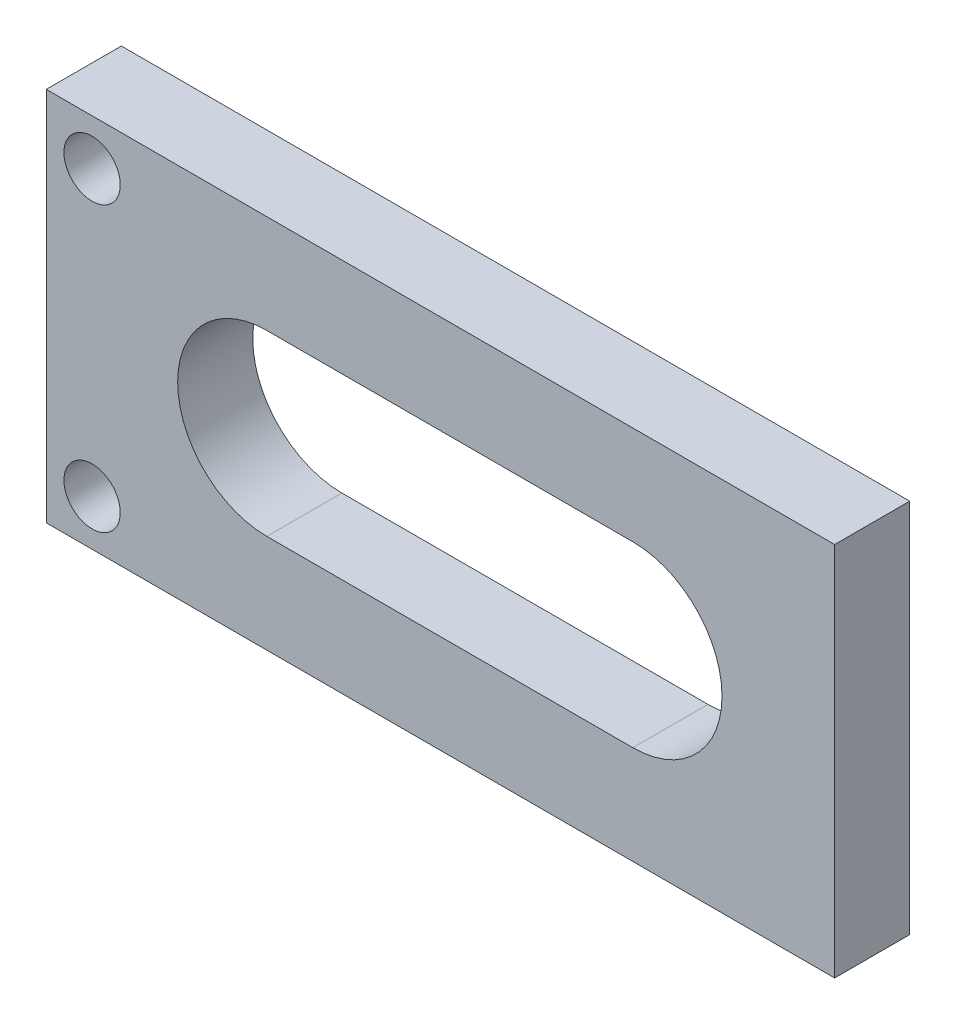
SolidWorks part; units mm, degrees
ref_plane "Front Plane" through (0, 0, 0) normal (0, 0, 1) x (1, 0, 0)
ref_plane "Top Plane" through (0, 0, 0) normal (0, 1, 0) x (1, 0, 0)
ref_plane "Right Plane" through (0, 0, 0) normal (1, 0, 0) x (0, 0, -1)
sketch "Sketch1" plane through (0, 0, 0) normal (0, 0, 1) x (1, 0, 0)
  line L0 (-9.25, 0) -> (10.25, 0) construction
  line L1 (-21, 10) -> (21, 10)
  line L2 (-21, 10) -> (-21, -10)
  line L3 (-21, -10) -> (21, -10)
  line L4 (21, 10) -> (21, -10)
  line L5 (-21, 10) -> (21, -10) construction
  line L6 (-21, -10) -> (21, 10) construction
  line L7 (-9.25, 4.75) -> (10.25, 4.75)
  line L8 (-9.25, -4.75) -> (10.25, -4.75)
  line L9 (55, 0) -> (-55, 0) construction
  arc A2 (-9.25, 4.75) -> (-9.25, -4.75) centre (-9.25, 0) ccw
  arc A3 (10.25, -4.75) -> (10.25, 4.75) centre (10.25, 0) ccw
  circle A4 centre (-18.5593, -7.5593) radius 2.4407 construction
  circle A5 centre (-18.5593, -7.5593) radius 1.5
  circle A6 centre (-18.5593, 7.5593) radius 1.5
  point P1 (0, 0)
  point P12 (0.5, 0)
  point P17 (-14, 0)
  dimension "D5" = 4.75
  dimension "D1" = 42
  dimension "D2" = 20
  dimension "D6" = 19.5
  dimension "D7" = 7
extrude "Boss-Extrude1" add sketch "Sketch1" along normal blind 4
